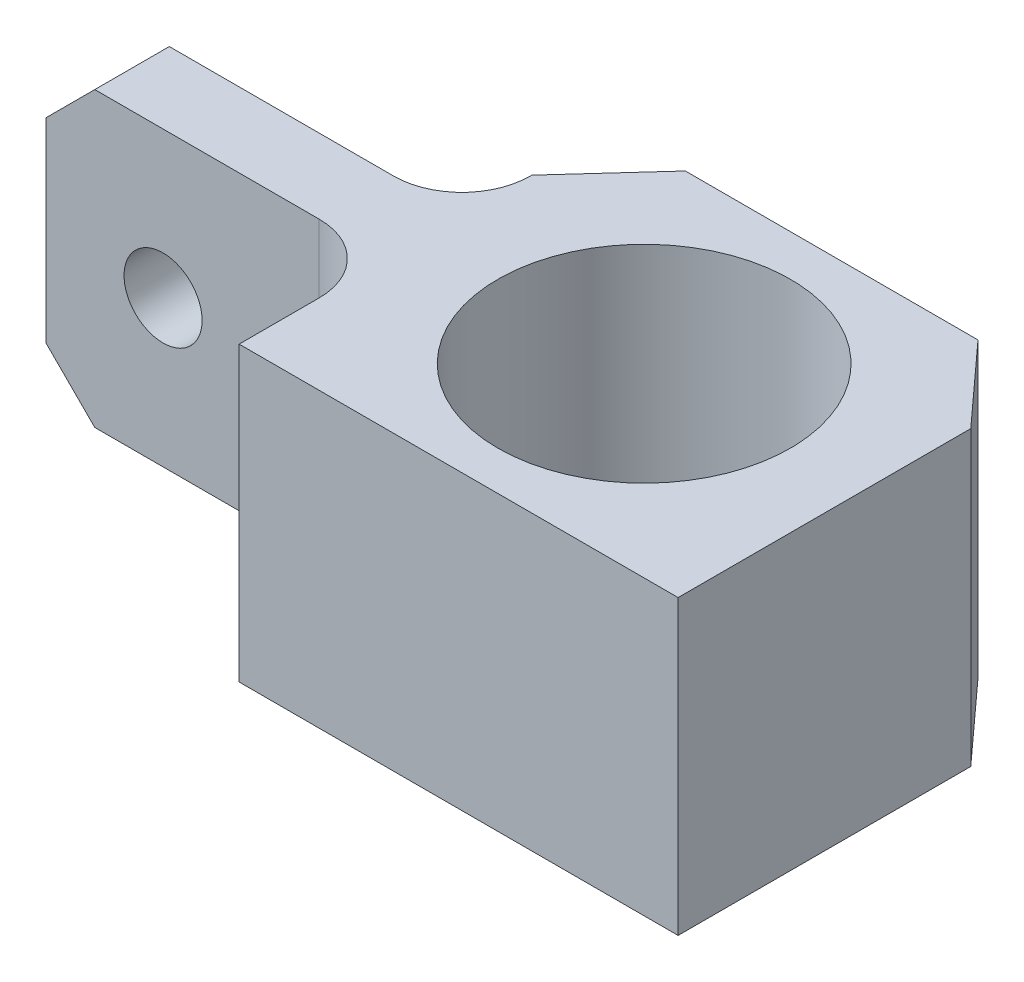
SolidWorks part; units mm, degrees
ref_plane "Спереди" through (0, 0, 0) normal (0, 0, 1) x (1, 0, 0)
ref_plane "Сверху" through (0, 0, 0) normal (0, 1, 0) x (1, 0, 0)
ref_plane "Справа" through (0, 0, 0) normal (1, 0, 0) x (0, 0, -1)
sketch "Эскиз1" plane through (0, 0, 0) normal (0, 1, 0) x (1, 0, 0)
  line L0 (-8.5273, 0) -> (45.8432, 0) construction
  line L1 (22.5, -19.0191) -> (-22.5, -19.0191)
  line L2 (-22.5, -19.0191) -> (-22.5, 10.9809)
  line L3 (-22.5, 10.9809) -> (-15, 19.2235)
  line L4 (-15, 19.2235) -> (15, 19.2235)
  line L8 (15, 19.2235) -> (22.5, 10.9809)
  line L9 (22.5, 10.9809) -> (22.5, -19.0191)
extrude "Вытянуть1" add sketch "Эскиз1" along normal blind 30
sketch "Эскиз2" plane through (0, 30, 0) normal (0, 1, 0) x (1, 0, 0)
  circle A0 centre (0, 0) radius 15
extrude "Вытянуть2" cut sketch "Эскиз2" against normal through all
sketch "Эскиз3" plane through (-22.5, 0, 0) normal (-1, 0, 0) x (0, 0, 1)
  line L1 (0, 0) -> (0, 34.0259) construction
  line L3 (-3.82, 30) -> (3.82, 30)
  line L4 (-3.82, 30) -> (-3.82, 0)
  line L5 (-3.82, 0) -> (3.82, 0)
  line L6 (3.82, 30) -> (3.82, 0)
  line L7 (0, 15) -> (26.1031, 15) construction
  line L8 (-3.82, 30) -> (3.82, 0) construction
  line L9 (-3.82, 0) -> (3.82, 30) construction
  point P1 (0, 15)
extrude "Вытянуть3" add sketch "Эскиз3" along normal blind 35
chamfer "Фаска1" distance 5 angle 45 2 edges at (-57.5, 0, 0) (-57.5, 30, 0)
sketch "Эскиз5" plane through (0, 0, 3.82) normal (0, 0, 1) x (1, 0, 0)
  line L0 (-57.5, 25) -> (-57.5, 5) construction
  circle A0 centre (-45.5, 15) radius 4
  dimension "D1" = 12
extrude "Вытянуть4" cut sketch "Эскиз5" against normal through all
fillet "Скругление2" radius 7 1 edges
fillet "Скругление3" radius 7 1 edges
